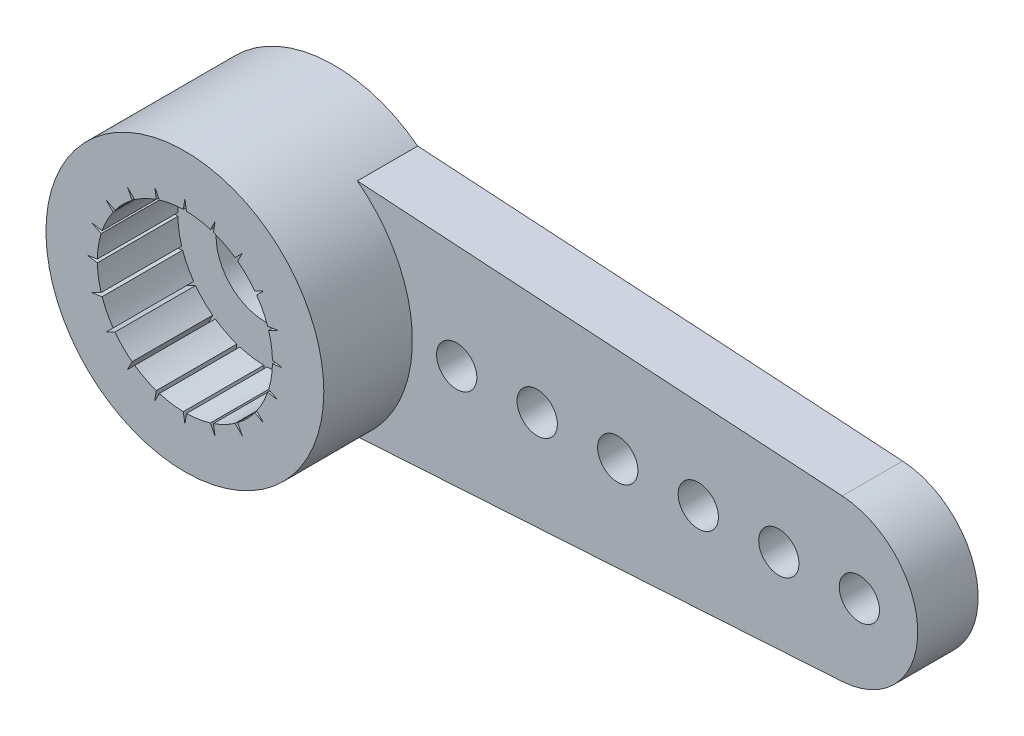
SolidWorks part; units mm, degrees
ref_plane "Front" through (0, 0, 0) normal (0, 0, 1) x (1, 0, 0)
ref_plane "Top" through (0, 0, 0) normal (0, 1, 0) x (1, 0, 0)
ref_plane "Right" through (0, 0, 0) normal (1, 0, 0) x (0, 0, -1)
sketch "草图1" plane through (0, 0, 0) normal (0, 0, 1) x (1, 0, 0)
  line L0 (-14.125, 1.9961) -> (-2.0833, 2.75)
  line L1 (-14, 0) -> (0, 0) construction
  line L2 (0, 0) -> (0, -6.6459) construction
  line L3 (-14.125, -1.9961) -> (-2.0833, -2.75)
  line L4 (14.125, -1.9961) -> (2.0833, -2.75)
  line L5 (14.125, 1.9961) -> (2.0833, 2.75)
  arc A0 (-2.0833, -2.75) -> (2.0833, -2.75) centre (0, 0) ccw
  arc A1 (-14.125, 1.9961) -> (-14.125, -1.9961) centre (-14, 0) ccw
  arc A2 (14.125, -1.9961) -> (14.125, 1.9961) centre (14, 0) ccw
  arc A3 (2.0833, 2.75) -> (-2.0833, 2.75) centre (0, 0) ccw
  dimension "D1" = 6.9
  dimension "D2" = 4
  dimension "D3" = 32
  dimension "D4" = 14
  dimension "D5" = 2.75
extrude "凸台-拉伸1" add sketch "草图1" along normal blind 1.5
sketch "草图2" plane through (0, 0, 1.5) normal (0, 0, 1) x (1, 0, 0)
  circle A0 centre (0, 0) radius 3.45
  arc A1 (2.0833, 2.75) -> (-2.0833, 2.75) centre (0, 0) ccw construction
extrude "凸台-拉伸2" add sketch "草图2" along normal blind 2.2
sketch "草图4" plane through (0, 0, 0) normal (0, 0, -1) x (-1, 0, 0)
  circle A0 centre (0, 0) radius 1.225
  dimension "D1" = 2.45
extrude "切除-拉伸2" cut sketch "草图4" against normal through all
sketch "草图3" plane through (0, 0, 3.7) normal (0, 0, 1) x (1, 0, 0)
  circle A0 centre (0, 0) radius 2.175
  dimension "D1" = 4.35
extrude "切除-拉伸1" cut sketch "草图3" against normal blind 2
sketch "草图5" plane through (0, 0, 3.7) normal (0, 0, 1) x (1, 0, 0)
  line L0 (0, 0) -> (2.425, 0) construction
  line L1 (2.425, 0) -> (1.7003, 0.1148)
  line L2 (2.425, 0) -> (1.7003, -0.1148)
  line L3 (1.7003, 0.1148) -> (1.7003, -0.1148)
  circle A4 centre (0, 0) radius 2.425
  circle A5 centre (0, 0) radius 2.425 construction
  dimension "D1" = 18
  dimension "D3" = 9
  dimension "D2" = 0.25
extrude "切除-拉伸3" cut sketch "草图5" against normal blind 2
pattern_circular "阵列(圆周)1" count 20 over 360 about axis through (0, 0, 0) along (0, 0, 1) of "切除-拉伸3"
sketch "草图6" plane through (0, 0, 0) normal (0, 0, -1) x (-1, 0, 0)
  circle A0 centre (0, 0) radius 2.35
  dimension "D1" = 4.7
extrude "切除-拉伸4" cut sketch "草图6" against normal blind 1
sketch "草图7" plane through (0, 0, 1.5) normal (0, 0, 1) x (1, 0, 0)
  circle A0 centre (-4.55, 0) radius 0.5
  circle A1 centre (-6.55, 0) radius 0.5
  circle A2 centre (-8.55, 0) radius 0.5
  circle A3 centre (-10.55, 0) radius 0.5
  circle A4 centre (-12.55, 0) radius 0.5
  circle A5 centre (-14.55, 0) radius 0.5
  dimension "D1" = 4.55
  dimension "D2" = 1
  dimension "D4" = 2
  dimension "D3" = 6
extrude "切除-拉伸5" cut sketch "草图7" against normal through all
mirror "镜向1" about plane through (0, 0, 0) normal (1, 0, 0) of "切除-拉伸5"
sketch "草图8" plane through (0, 0, 3.7) normal (0, 0, 1) x (1, 0, 0)
  line L0 (-2.0833, 2.75) -> (-16, 2.75)
  line L1 (-16, 2.75) -> (-16, -2.75)
  line L2 (-16, -2.75) -> (-2.0833, -2.75)
  arc A0 (-2.0833, 2.75) -> (-2.0833, -2.75) centre (0, 0) ccw construction
  arc A1 (-2.0833, 2.75) -> (-2.0833, -2.75) centre (0, 0) ccw
  arc A2 (-14.125, 1.9961) -> (-14.125, -1.9961) centre (-14, 0) ccw construction
extrude "切除-拉伸6" cut sketch "草图8" against normal through all
